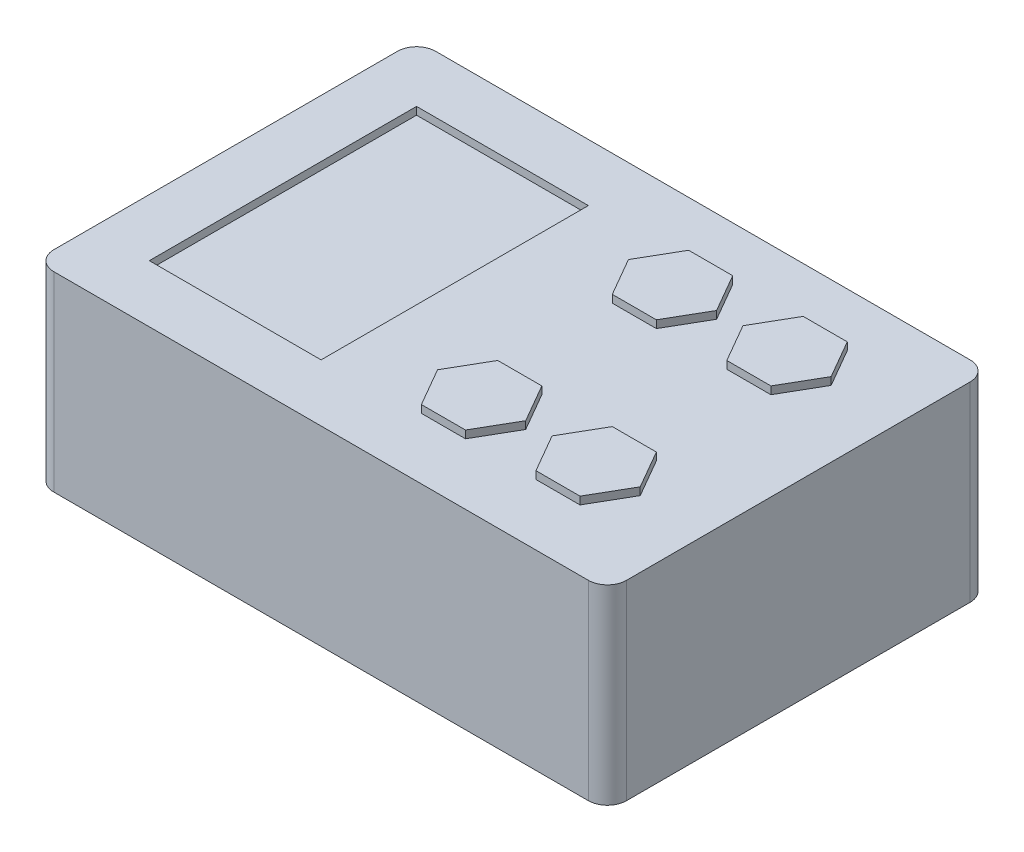
SolidWorks part; units mm, degrees
material "Stainless Steel (ferritic)"
ref_plane "Front Plane" through (0, 0, 0) normal (0, 0, 1) x (1, 0, 0)
ref_plane "Top Plane" through (0, 0, 0) normal (0, 1, 0) x (1, 0, 0)
ref_plane "Right Plane" through (0, 0, 0) normal (1, 0, 0) x (0, 0, -1)
sketch "Sketch1" plane through (0, 0, 0) normal (0, 1, 0) x (1, 0, 0)
  line L1 (-75, 50) -> (75, 50)
  line L2 (-75, 50) -> (-75, -50)
  line L3 (-75, -50) -> (75, -50)
  line L4 (75, 50) -> (75, -50)
  line L5 (-75, 50) -> (75, -50) construction
  line L6 (-75, -50) -> (75, 50) construction
  point P0 (0, 0)
  dimension "D1" = 150
  dimension "D2" = 100
extrude "Boss-Extrude1" add sketch "Sketch1" along normal blind 50
shell "Shell1" thickness 3
sketch "Sketch3" plane through (0, 0, 0) normal (0, -1, 0) x (1, 0, 0)
  line L0 (75, 50) -> (75, -50) construction
  line L1 (-75, -50) -> (-75, 50) construction
  circle A0 centre (37, 0) radius 30
  circle A1 centre (-37, 0) radius 30
  dimension "D1" = 60
  dimension "D2" = 38
  dimension "D3" = 60
  dimension "D4" = 38
extrude "Cut-Extrude2" cut sketch "Sketch3" against normal blind 5
sketch "Sketch4" plane through (0, 50, 0) normal (0, 1, 0) x (1, 0, 0)
  line L0 (-75, 50) -> (-75, -50) construction
  line L1 (-60, 35) -> (-15, 35)
  line L2 (-60, 35) -> (-60, -35)
  line L3 (-60, -35) -> (-15, -35)
  line L4 (-15, 35) -> (-15, -35)
  line L5 (-60, 35) -> (-15, -35) construction
  line L6 (-60, -35) -> (-15, 35) construction
  point P0 (-37.5, 0)
  dimension "D1" = 0
  dimension "D2" = 70
  dimension "35" = 45
  dimension "D3" = 15
extrude "Cut-Extrude3" cut sketch "Sketch4" against normal blind 2
sketch "Sketch5" plane through (0, 50, 0) normal (0, 1, 0) x (1, 0, 0)
  line L0 (57.5886, -24) -> (51.8151, -14)
  line L1 (27.5886, -24) -> (21.8151, -14)
  line L2 (21.8151, -14) -> (10.2681, -14)
  line L3 (10.2681, -14) -> (4.4946, -24)
  line L4 (4.4946, -24) -> (10.2681, -34)
  line L5 (10.2681, -34) -> (21.8151, -34)
  line L6 (21.8151, -34) -> (27.5886, -24)
  line L7 (51.8151, -14) -> (40.2681, -14)
  line L8 (40.2681, -14) -> (34.4946, -24)
  line L9 (34.4946, -24) -> (40.2681, -34)
  line L10 (40.2681, -34) -> (51.8151, -34)
  line L11 (51.8151, -34) -> (57.5886, -24)
  line L12 (57.5886, 26) -> (51.8151, 36)
  line L13 (51.8151, 36) -> (40.2681, 36)
  line L14 (40.2681, 36) -> (34.4946, 26)
  line L15 (34.4946, 26) -> (40.2681, 16)
  line L16 (40.2681, 16) -> (51.8151, 16)
  line L17 (51.8151, 16) -> (57.5886, 26)
  line L18 (27.5886, 26) -> (21.8151, 36)
  line L19 (21.8151, 36) -> (10.2681, 36)
  line L20 (10.2681, 36) -> (4.4946, 26)
  line L21 (4.4946, 26) -> (10.2681, 16)
  line L22 (10.2681, 16) -> (21.8151, 16)
  line L23 (21.8151, 16) -> (27.5886, 26)
  line L24 (-75, -50) -> (75, -50) construction
  circle A0 centre (16.0416, -24) radius 10 construction
  dimension "D4" = 20
  dimension "D3" = 16
  dimension "D1" = 2
  dimension "D2" = 2
extrude "Boss-Extrude2" add sketch "Sketch5" along normal blind 2
fillet "Fillet1" radius 5 4 edges at (-75, 25, -50) (75, 25, -50) (75, 25, 50) (-75, 25, 50)
